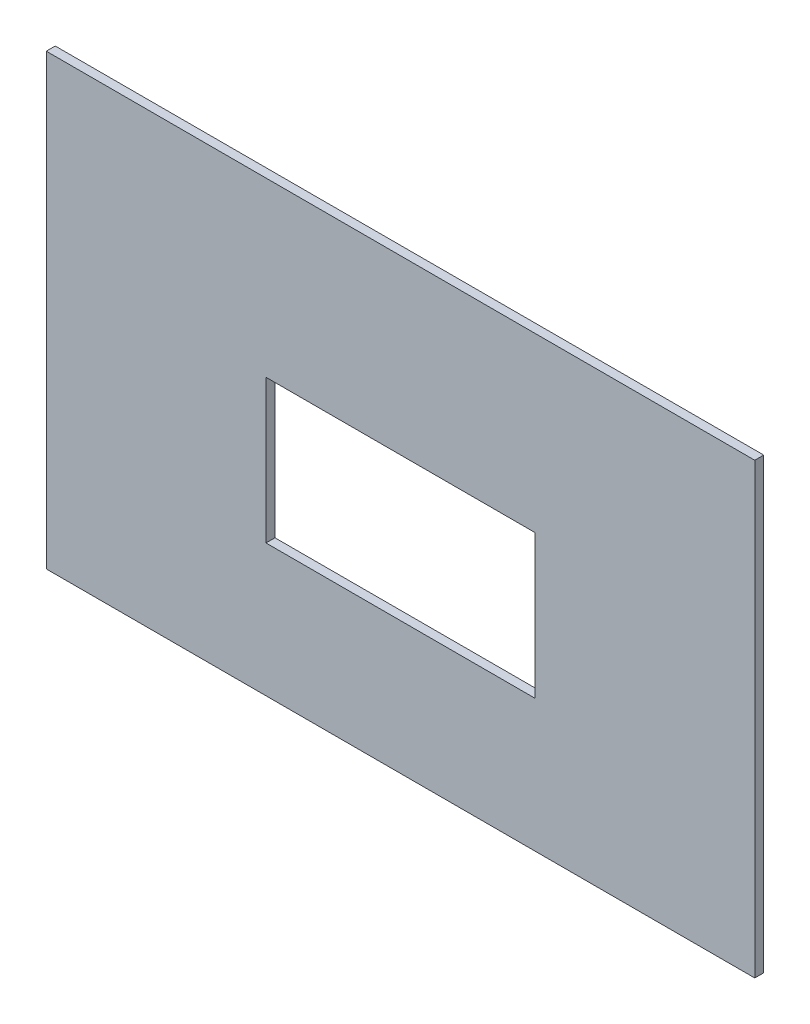
SolidWorks part; units mm, degrees
ref_plane "Front Plane" through (0, 0, 0) normal (0, 0, 1) x (1, 0, 0)
ref_plane "Top Plane" through (0, 0, 0) normal (0, 1, 0) x (1, 0, 0)
ref_plane "Right Plane" through (0, 0, 0) normal (1, 0, 0) x (0, 0, -1)
sketch "Sketch1" plane through (0, 0, 0) normal (0, 0, 1) x (1, 0, 0)
  line L1 (-405.4726, 195.2736) -> (384.5274, 195.2736)
  line L2 (-405.4726, 195.2736) -> (-405.4726, -304.7264)
  line L3 (-405.4726, -304.7264) -> (384.5274, -304.7264)
  line L4 (384.5274, 195.2736) -> (384.5274, -304.7264)
  dimension "D1" = 790
  dimension "D2" = 500
extrude "Boss-Extrude1" add sketch "Sketch1" along normal blind 10
sketch "Sketch3" plane through (0, 0, 0) normal (0, 0, -1) x (-1, 0, 0)
  line L1 (160.4726, 2.8736) -> (-139.5274, 2.8736)
  line L2 (160.4726, 2.8736) -> (160.4726, -157.1264)
  line L3 (160.4726, -157.1264) -> (-139.5274, -157.1264)
  line L4 (-139.5274, 2.8736) -> (-139.5274, -157.1264)
extrude "Cut-Extrude1" cut sketch "Sketch3" against normal blind 10
